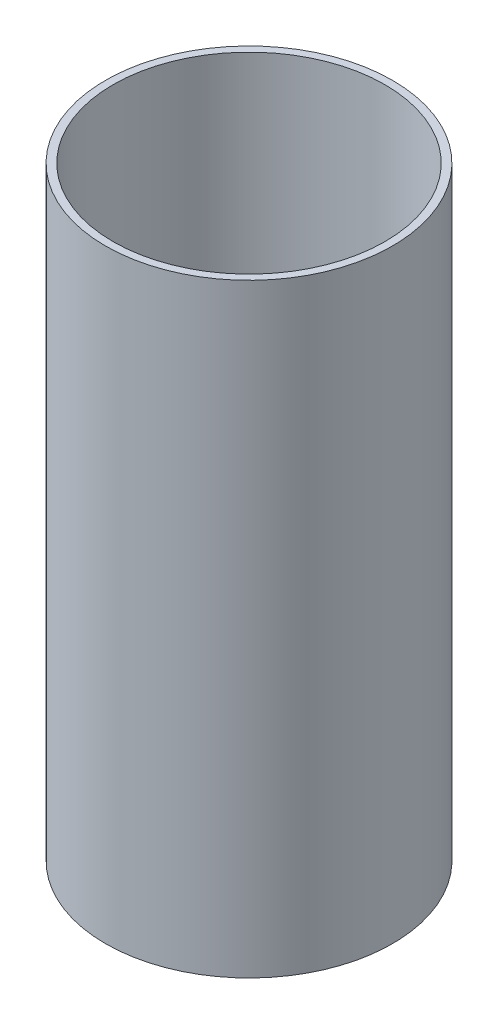
SolidWorks part; units mm, degrees
ref_plane "Front Plane" through (0, 0, 0) normal (0, 0, 1) x (1, 0, 0)
ref_plane "Top Plane" through (0, 0, 0) normal (0, 1, 0) x (1, 0, 0)
ref_plane "Right Plane" through (0, 0, 0) normal (1, 0, 0) x (0, 0, -1)
sketch "Sketch2" plane through (0, 0, 0) normal (0, 1, 0) x (1, 0, 0)
  circle A0 centre (0, 0) radius 36
  circle A1 centre (0, 0) radius 38
  dimension "D1" = 2
  dimension "D2" = 76
extrude "Boss-Extrude1" add sketch "Sketch2" along normal blind 160
